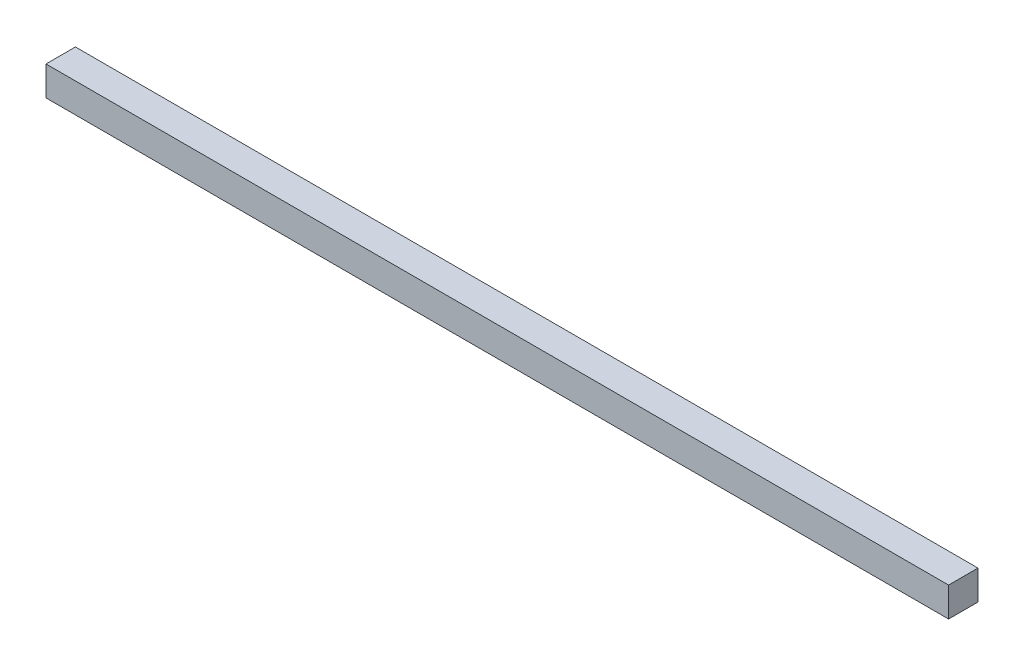
SolidWorks part; units mm, degrees
material "Pine"
ref_plane "Front Plane" through (0, 0, 0) normal (0, 0, 1) x (1, 0, 0)
ref_plane "Top Plane" through (0, 0, 0) normal (0, 1, 0) x (1, 0, 0)
ref_plane "Right Plane" through (0, 0, 0) normal (1, 0, 0) x (0, 0, -1)
sketch "Sketch1" plane through (0, 0, 0) normal (0, 0, 1) x (1, 0, 0)
  line L1 (-584.2, 19.05) -> (584.2, 19.05)
  line L2 (-584.2, 19.05) -> (-584.2, -19.05)
  line L3 (-584.2, -19.05) -> (584.2, -19.05)
  line L4 (584.2, 19.05) -> (584.2, -19.05)
  point P4 (0, 19.05)
  point P6 (584.2, 0)
  dimension "D1" = 1168.4
  dimension "D2" = 38.1
extrude "Boss-Extrude1" add sketch "Sketch1" along normal blind 38.1
